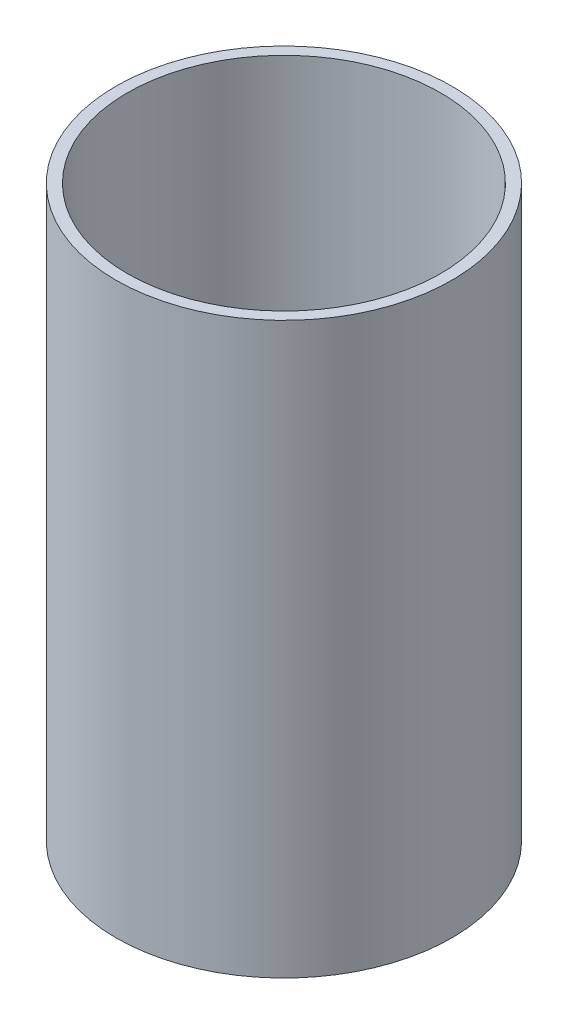
SolidWorks part; units mm, degrees
material "PVC 0.007 Plasticized"
ref_plane "Front Plane" through (0, 0, 0) normal (0, 0, 1) x (1, 0, 0)
ref_plane "Top Plane" through (0, 0, 0) normal (0, 1, 0) x (1, 0, 0)
ref_plane "Right Plane" through (0, 0, 0) normal (1, 0, 0) x (0, 0, -1)
sketch "Sketch1" plane through (0, 0, 0) normal (0, 1, 0) x (1, 0, 0)
  circle A0 centre (0, 0) radius 37.465
  circle A1 centre (0, 0) radius 34.925
  dimension "D1" = 74.93
  dimension "D2" = 69.85
extrude "Boss-Extrude1" add sketch "Sketch1" along normal blind 127
